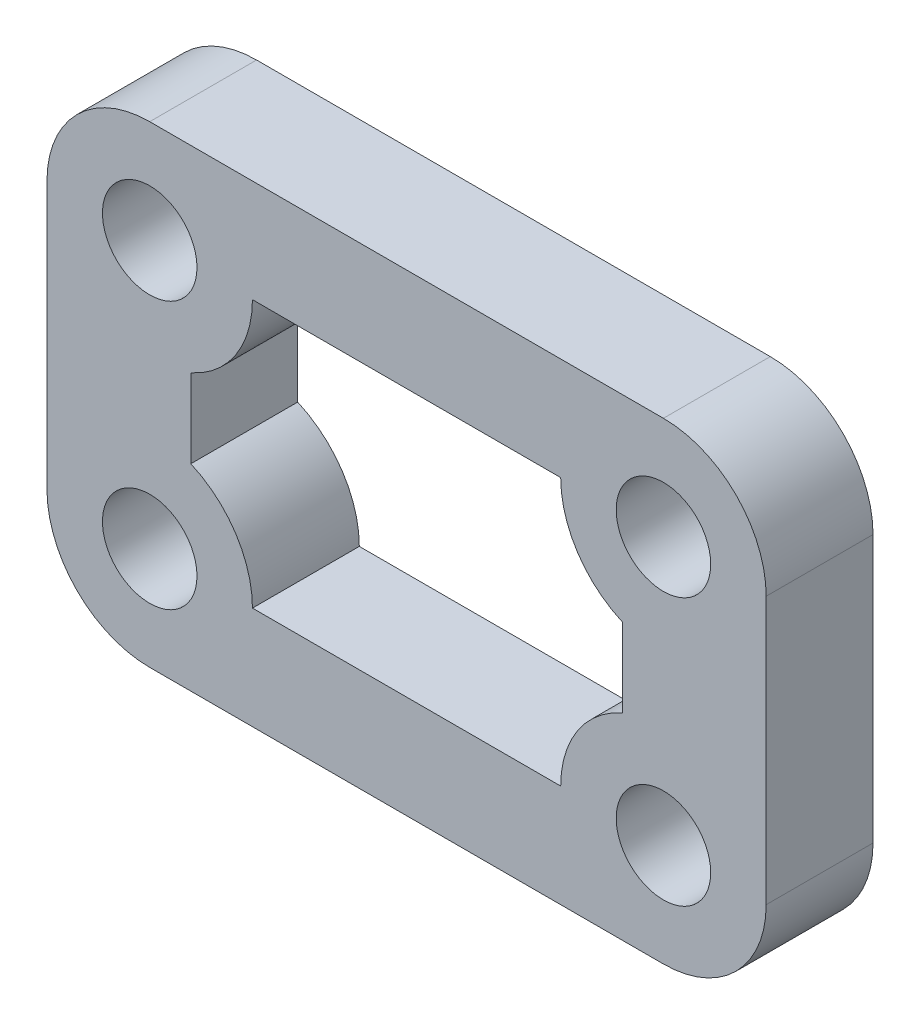
SolidWorks part; units mm, degrees
ref_plane "前视基准面" through (0, 0, 0) normal (0, 0, 1) x (1, 0, 0)
ref_plane "上视基准面" through (0, 0, 0) normal (0, 1, 0) x (1, 0, 0)
ref_plane "右视基准面" through (0, 0, 0) normal (1, 0, 0) x (0, 0, -1)
sketch "草图1" plane through (0, 0, 0) normal (0, 0, 1) x (1, 0, 0)
  line L0 (-5, 13) -> (-5, 0)
  line L1 (0, 0) -> (25, 0) construction
  line L2 (0, 0) -> (0, 13) construction
  line L3 (0, 13) -> (25, 13) construction
  line L4 (25, 0) -> (25, 13) construction
  line L5 (0, -5) -> (25, -5)
  line L6 (25, 18) -> (0, 18)
  line L7 (30, 13) -> (30, 0)
  line L8 (5, 13) -> (20, 13)
  line L9 (5, 0) -> (20, 0)
  line L10 (2, 8.4174) -> (2, 4.5826)
  line L11 (23, 8.4174) -> (23, 4.5826)
  circle A0 centre (0, 13) radius 2.3
  circle A1 centre (25, 13) radius 2.3
  circle A2 centre (0, 0) radius 2.3
  circle A3 centre (25, 0) radius 2.3
  arc A4 (2, 8.4174) -> (5, 13) centre (0, 13) ccw
  arc A5 (5, 0) -> (2, 4.5826) centre (0, 0) ccw
  arc A6 (23, 4.5826) -> (20, 0) centre (25, 0) ccw
  arc A7 (20, 13) -> (23, 8.4174) centre (25, 13) ccw
  arc A8 (0, 18) -> (-5, 13) centre (0, 13) ccw
  arc A9 (30, 13) -> (25, 18) centre (25, 13) ccw
  arc A10 (25, -5) -> (30, 0) centre (25, 0) ccw
  arc A11 (-5, 0) -> (0, -5) centre (0, 0) ccw
  dimension "D3" = 4.6
  dimension "D4" = 10
  dimension "D1" = 13
  dimension "D2" = 25
  dimension "D5" = 2
  dimension "D6" = 2
extrude "凸台-拉伸1" add sketch "草图1" along normal blind 5.2
